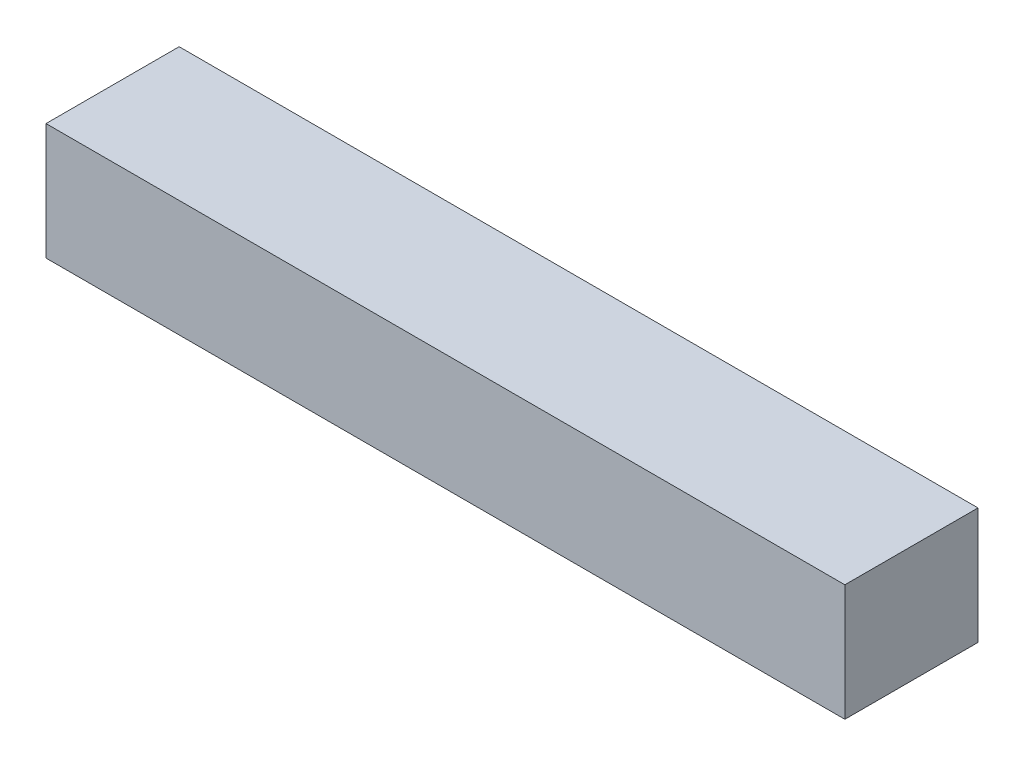
SolidWorks part; units mm, degrees
ref_plane "Front Plane" through (0, 0, 0) normal (0, 0, 1) x (1, 0, 0)
ref_plane "Top Plane" through (0, 0, 0) normal (0, 1, 0) x (1, 0, 0)
ref_plane "Right Plane" through (0, 0, 0) normal (1, 0, 0) x (0, 0, -1)
sketch "Sketch1" plane through (0, 0, 0) normal (0, 1, 0) x (1, 0, 0)
  line L1 (0, 0) -> (304.8, 0)
  line L2 (0, 0) -> (0, 50.8)
  line L3 (0, 50.8) -> (304.8, 50.8)
  line L4 (304.8, 0) -> (304.8, 50.8)
  dimension "D1" = 50.8
  dimension "D2" = 304.8
extrude "Boss-Extrude1" add sketch "Sketch1" along normal blind 44.45
